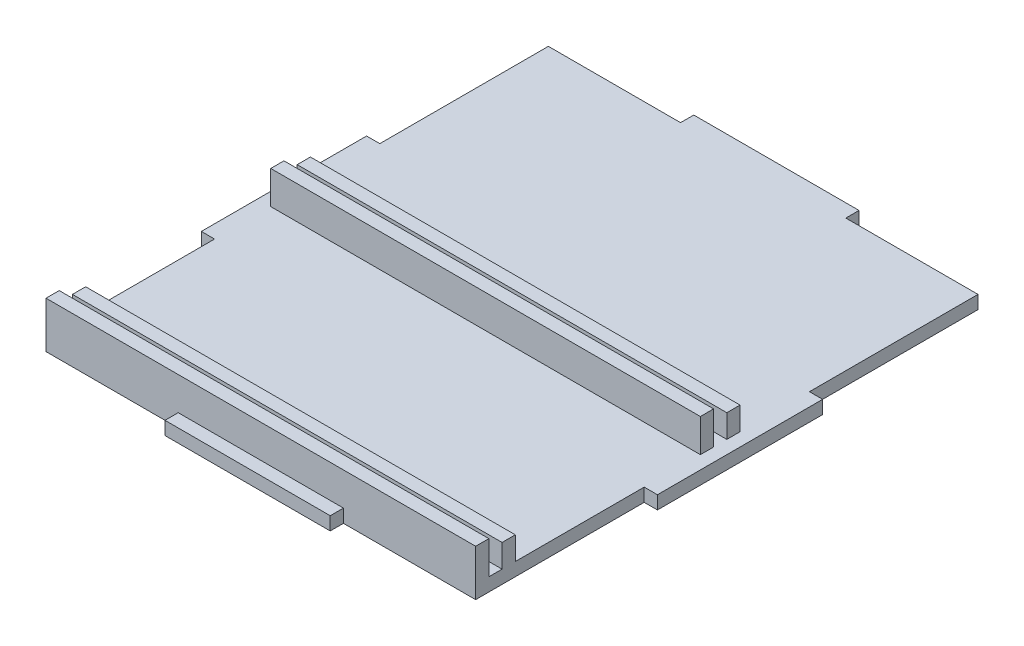
SolidWorks part; units mm, degrees
ref_plane "Front Plane" through (0, 0, 0) normal (0, 0, 1) x (1, 0, 0)
ref_plane "Top Plane" through (0, 0, 0) normal (0, 1, 0) x (1, 0, 0)
ref_plane "Right Plane" through (0, 0, 0) normal (1, 0, 0) x (0, 0, -1)
sketch "Sketch3" plane through (0, 0, 0) normal (0, 1, 0) x (1, 0, 0)
  line L0 (-25, 80) -> (25, 80)
  line L1 (-69, 25) -> (-69, -25)
  line L2 (-25, -80) -> (25, -80)
  line L3 (69, -25) -> (69, 25)
  line L4 (-25, -80) -> (-25, -76)
  line L5 (-25, -76) -> (-65, -76)
  line L6 (25, -80) -> (25, -76)
  line L7 (25, -76) -> (65, -76)
  line L8 (-25, 80) -> (-25, 76)
  line L9 (-25, 76) -> (-65, 76)
  line L10 (25, 80) -> (25, 76)
  line L11 (25, 76) -> (65, 76)
  line L12 (-65, 76) -> (-65, 25)
  line L13 (65, 76) -> (65, 25)
  line L14 (-69, -25) -> (-65, -25)
  line L15 (-69, 25) -> (-65, 25)
  line L16 (65, 25) -> (69, 25)
  line L17 (65, -25) -> (69, -25)
  line L18 (-65, -25) -> (-65, -76)
  line L19 (65, -25) -> (65, -76)
  dimension "D2" = 69
  dimension "D3" = 69
  dimension "D4" = 80
  dimension "D5" = 50
  dimension "D6" = 4
  dimension "D7" = 4
  dimension "D8" = 25
  dimension "D9" = 4
  dimension "D10" = 4
  dimension "D11" = 50
  dimension "D12" = 25
  dimension "D13" = 80
  dimension "D14" = 4
  dimension "D15" = 4
  dimension "D16" = 50
  dimension "D17" = 25
  dimension "D18" = 50
extrude "Boss-Extrude1" add sketch "Sketch3" along normal blind 4
sketch "Sketch4" plane through (0, 4, 0) normal (0, 1, 0) x (1, 0, 0)
  line L0 (-65, -76) -> (65, -76)
  line L1 (-65, -25) -> (-65, -76) construction
  line L2 (65, -76) -> (65, -25) construction
  line L3 (-65, -76) -> (-65, -72)
  line L4 (-65, -72) -> (65, -72)
  line L5 (65, -72) -> (65, -76)
  dimension "D1" = 4
extrude "Boss-Extrude2" add sketch "Sketch4" along normal blind 10
sketch "Sketch5" plane through (0, 4, 0) normal (0, 1, 0) x (1, 0, 0)
  line L0 (-65, -68) -> (-65, -64)
  line L1 (-65, -25) -> (-65, -72) construction
  line L2 (-65, -64) -> (65, -64)
  line L3 (65, -72) -> (65, -25) construction
  line L4 (65, -64) -> (65, -68)
  line L5 (65, -68) -> (-65, -68)
  line L6 (65, -72) -> (-65, -72) construction
  dimension "D1" = 4
  dimension "D2" = 4
extrude "Boss-Extrude3" add sketch "Sketch5" along normal blind 7
sketch "Sketch6" plane through (0, 4, 0) normal (0, 1, 0) x (1, 0, 0)
  line L0 (-65, -4) -> (-65, -8)
  line L1 (-65, 76) -> (-65, 25) construction
  line L2 (-65, -8) -> (65, -8)
  line L3 (65, 25) -> (65, 76) construction
  line L4 (65, -8) -> (65, -4)
  line L5 (65, -4) -> (-65, -4)
  line L6 (65, -64) -> (-65, -64) construction
  dimension "D1" = 4
  dimension "D2" = 56
extrude "Boss-Extrude4" add sketch "Sketch6" along normal blind 10
sketch "Sketch7" plane through (0, 4, 0) normal (0, 1, 0) x (1, 0, 0)
  line L0 (-65, 4) -> (-65, 0)
  line L1 (-65, 76) -> (-65, 25) construction
  line L2 (-65, 0) -> (65, 0)
  line L3 (65, 25) -> (65, 76) construction
  line L4 (65, 0) -> (65, 4)
  line L5 (65, 4) -> (-65, 4)
  line L6 (65, -4) -> (-65, -4) construction
  dimension "D1" = 4
  dimension "D2" = 4
extrude "Boss-Extrude5" add sketch "Sketch7" along normal blind 7
